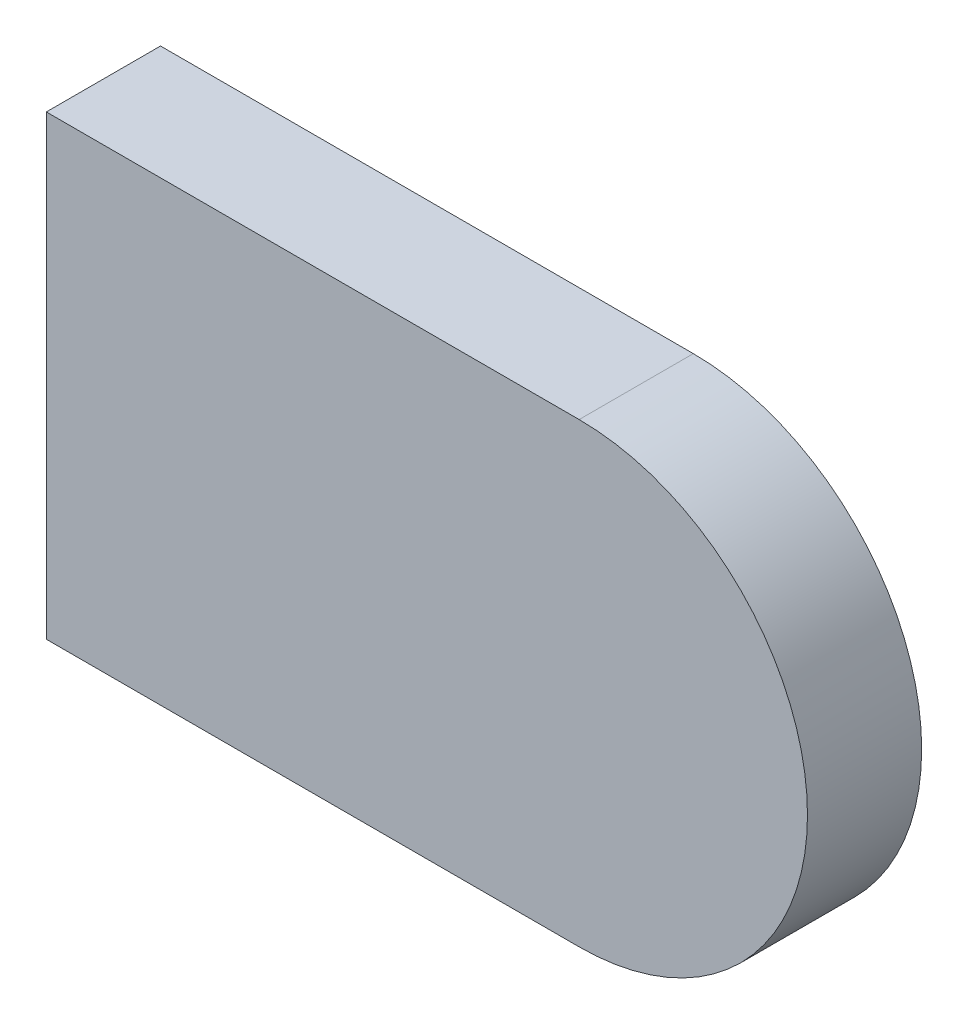
SolidWorks part; units mm, degrees
ref_plane "Front" through (0, 0, 0) normal (0, 0, 1) x (1, 0, 0)
ref_plane "Top" through (0, 0, 0) normal (0, 1, 0) x (1, 0, 0)
ref_plane "Right" through (0, 0, 0) normal (1, 0, 0) x (0, 0, -1)
sketch "Sketch1" plane through (0, 0, 0) normal (0, 0, 1) x (1, 0, 0)
  line L1 (0, 0) -> (88.9034, 0)
  line L2 (0, 0) -> (0, 76.2)
  line L3 (0, 76.2) -> (88.9, 76.2)
  arc A0 (88.9, 76.2) -> (126.9966, 38.0942) centre (88.8966, 38.1) cw
  arc A1 (126.9966, 38.0942) -> (88.9034, 0) centre (88.8966, 38.1) cw
  dimension "D5" = 38.1
  dimension "D3" = 38.1
  dimension "D1" = 88.9
  dimension "D2" = 88.9034
  dimension "D4" = 76.2
  dimension "D6" = 38.1
extrude "Boss-Extrude1" add sketch "Sketch1" along normal blind 19.05
